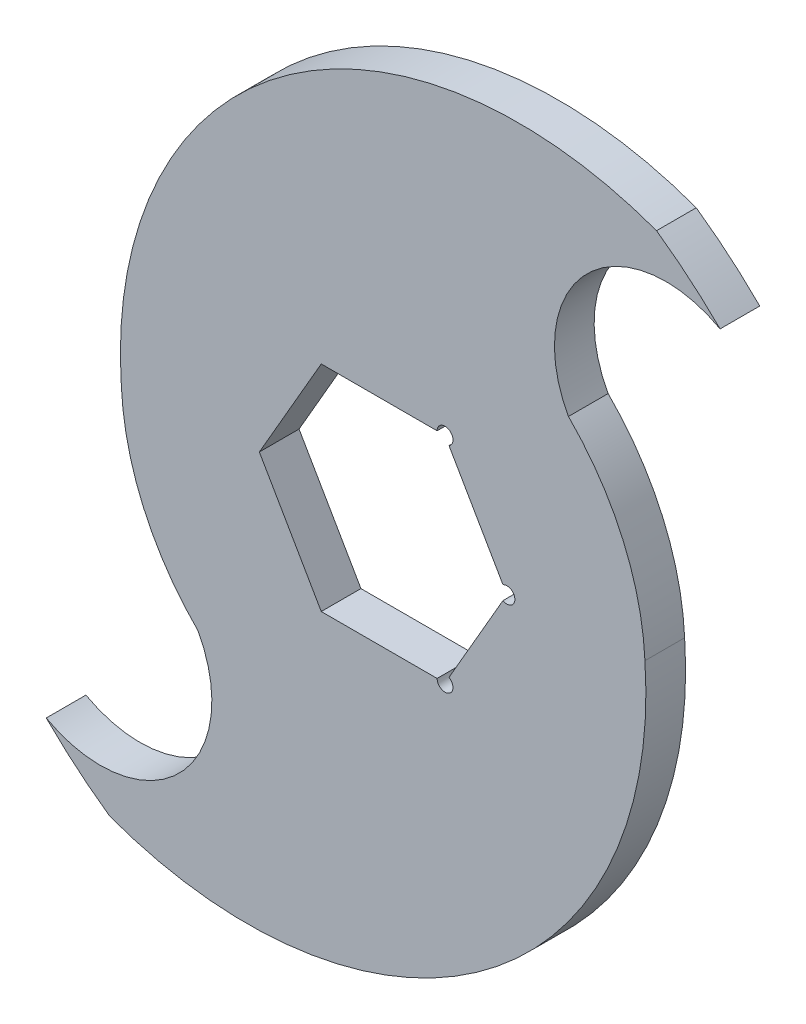
SolidWorks part; units mm, degrees
ref_plane "Front" through (0, 0, 0) normal (0, 0, 1) x (1, 0, 0)
ref_plane "Top" through (0, 0, 0) normal (0, 1, 0) x (1, 0, 0)
ref_plane "Right" through (0, 0, 0) normal (1, 0, 0) x (0, 0, -1)
sketch "Model" plane through (0, 0, 0) normal (0, 0, 1) x (1, 0, 0)
  line L0 (788.0621, 66.9396) -> (781.2678, 78.7076)
  line L1 (779.7678, 79.5736) -> (765.1794, 79.5736)
  line L2 (765.1794, 79.5736) -> (757.3851, 66.0736)
  line L3 (757.3851, 66.0736) -> (765.1794, 52.5736)
  line L4 (765.1794, 52.5736) -> (779.7678, 52.5736)
  line L5 (781.2678, 53.4396) -> (788.0621, 65.2076)
  arc A0 (807.4, 115.2144) -> (740.0085, 64.5572) centre (790.1, 68.0738) ccw
  arc A1 (740.0085, 64.5572) -> (749.6391, 42.7391) centre (772.9736, 66.0736) ccw
  arc A2 (730.5472, 23.6472) -> (749.6391, 42.7391) centre (737.3637, 35.9226) ccw
  arc A3 (730.5472, 23.6472) -> (738.5472, 16.9328) centre (772.9736, 66.0736) ccw
  arc A4 (738.5472, 16.9328) -> (805.9387, 67.59) centre (755.8472, 64.0734) ccw
  arc A5 (805.9387, 67.59) -> (796.3081, 89.4081) centre (772.9736, 66.0736) ccw
  arc A6 (815.4, 108.5) -> (796.3081, 89.4081) centre (808.5835, 96.2246) ccw
  arc A7 (815.4, 108.5) -> (807.4, 115.2144) centre (772.9736, 66.0736) ccw
  arc A8 (781.2678, 78.7076) -> (779.7678, 79.5736) centre (780.7678, 79.5736) ccw
  arc A9 (779.7678, 52.5736) -> (781.2678, 53.4396) centre (780.7678, 52.5736) ccw
  arc A10 (788.0621, 65.2076) -> (788.0621, 66.9396) centre (788.5621, 66.0736) ccw
extrude "Boss-Extrude1" add sketch "Model" along normal mid plane 5
